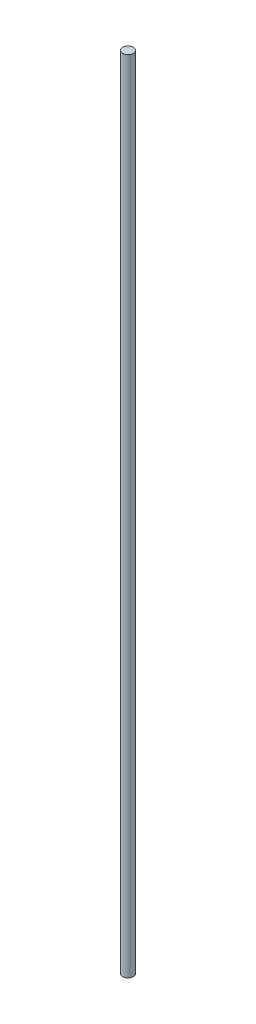
SolidWorks part; units mm, degrees
ref_plane "Front Plane" through (0, 0, 0) normal (0, 0, 1) x (1, 0, 0)
ref_plane "Top Plane" through (0, 0, 0) normal (0, 1, 0) x (1, 0, 0)
ref_plane "Right Plane" through (0, 0, 0) normal (1, 0, 0) x (0, 0, -1)
sketch "Sketch2" plane through (0, 0, 0) normal (0, 1, 0) x (1, 0, 0)
  circle A0 centre (0, 0) radius 0.405
  dimension "D1" = 0.81
extrude "Boss-Extrude1" add sketch "Sketch2" along normal blind 60.8
